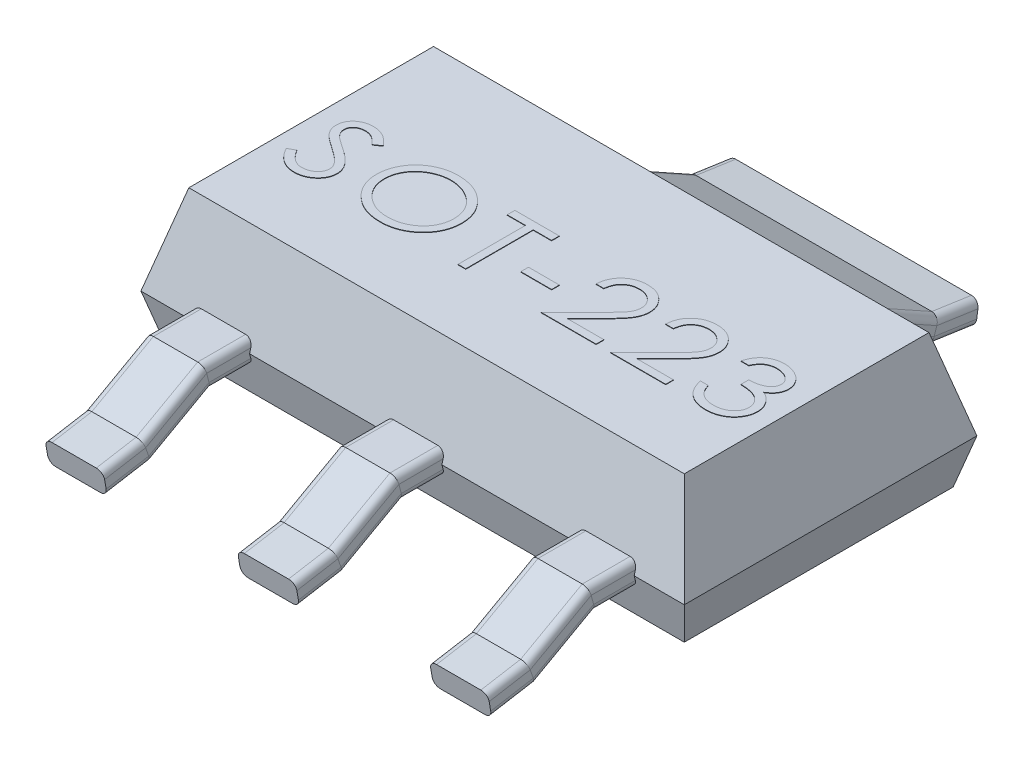
SolidWorks part; units mm, degrees
ref_plane "Front Plane" through (0, 0, 0) normal (0, 0, 1) x (1, 0, 0)
ref_plane "Top Plane" through (0, 0, 0) normal (0, 1, 0) x (1, 0, 0)
ref_plane "Right Plane" through (0, 0, 0) normal (1, 0, 0) x (0, 0, -1)
sketch "Sketch1" plane through (0, 0, 0) normal (0, 1, 0) x (1, 0, 0)
  line L0 (0, 73.9707) -> (0, -64.157) construction
  line L1 (-93.9661, 0) -> (112.1215, 0) construction
  line L3 (3.25, -1.75) -> (-3.25, -1.75)
  line L4 (3.25, -1.75) -> (3.25, 1.75)
  line L5 (3.25, 1.75) -> (-3.25, 1.75)
  line L6 (-3.25, -1.75) -> (-3.25, 1.75)
  line L7 (3.25, -1.75) -> (-3.25, 1.75) construction
  line L8 (3.25, 1.75) -> (-3.25, -1.75) construction
  point P5 (0, 0)
  dimension "D1" = 3.5
  dimension "D2" = 6.5
extrude "Boss-Extrude1" add sketch "Sketch1" along normal blind 1.07 draft 15 and the other way blind 0.53 draft 15
ref_plane "Plane1" through (0, 0, 1.608) normal (0, 0, 1) x (1, 0, 0)
sketch "Sketch4" plane through (0, 0, 1.608) normal (0, 0, 1) x (1, 0, 0)
  line L0 (-3.25, 0) -> (3.25, 0) construction
  line L1 (0.2646, -0.14) -> (-0.2646, -0.14)
  line L2 (0.35, -0.0546) -> (0.35, 0.0546)
  line L3 (0.2646, 0.14) -> (-0.2646, 0.14)
  line L4 (-0.35, -0.0546) -> (-0.35, 0.0546)
  line L5 (0.35, -0.14) -> (-0.35, 0.14) construction
  line L6 (0.35, 0.14) -> (-0.35, -0.14) construction
  line L7 (2.5646, -0.14) -> (2.0354, -0.14)
  line L8 (-2.5646, 0.14) -> (-2.0354, 0.14)
  line L9 (-2.65, 0.0546) -> (-2.65, -0.0546)
  line L10 (-2.5646, -0.14) -> (-2.0354, -0.14)
  line L11 (-1.95, 0.0546) -> (-1.95, -0.0546)
  line L12 (-2.65, 0.14) -> (-1.95, -0.14) construction
  line L13 (-2.65, -0.14) -> (-1.95, 0.14) construction
  line L14 (1.95, 0.0546) -> (1.95, -0.0546)
  line L15 (2.65, 0.0546) -> (2.65, -0.0546)
  line L16 (2.5646, 0.14) -> (2.0354, 0.14)
  line L17 (0, 0.7388) -> (0, -0.4269) construction
  arc A0 (2.65, 0.0546) -> (2.5646, 0.14) centre (2.5646, 0.0546) ccw
  arc A1 (2.65, -0.0546) -> (2.5646, -0.14) centre (2.5646, -0.0546) cw
  arc A2 (0.2646, 0.14) -> (0.35, 0.0546) centre (0.2646, 0.0546) cw
  arc A3 (0.35, -0.0546) -> (0.2646, -0.14) centre (0.2646, -0.0546) cw
  arc A4 (-0.35, -0.0546) -> (-0.2646, -0.14) centre (-0.2646, -0.0546) ccw
  arc A5 (-0.35, 0.0546) -> (-0.2646, 0.14) centre (-0.2646, 0.0546) cw
  arc A6 (-2.5646, 0.14) -> (-2.65, 0.0546) centre (-2.5646, 0.0546) ccw
  arc A7 (-2.65, -0.0546) -> (-2.5646, -0.14) centre (-2.5646, -0.0546) ccw
  arc A8 (-1.95, -0.0546) -> (-2.0354, -0.14) centre (-2.0354, -0.0546) cw
  arc A9 (-1.95, 0.0546) -> (-2.0354, 0.14) centre (-2.0354, 0.0546) ccw
  arc A10 (2.0354, 0.14) -> (1.95, 0.0546) centre (2.0354, 0.0546) ccw
  arc A11 (1.95, -0.0546) -> (2.0354, -0.14) centre (2.0354, -0.0546) ccw
  point P2 (0, 0)
  point P7 (-2.3, 0)
  point P19 (0, 0)
  dimension "D5" = 0.0854
  dimension "D6" = 0.0854
  dimension "D1" = 0.28
  dimension "D2" = 0.7
  dimension "D3" = 0.28
  dimension "D4" = 0.7
sketch "Sketch6" plane through (0, 0, 0) normal (1, 0, 0) x (0, 0, -1)
  line L0 (-1.75, 0) -> (1.75, 0) construction
  line L1 (-1.608, 0) -> (-2.2492, 0)
  line L2 (-2.2492, 0) -> (-2.975, -0.4047)
  line L3 (-2.975, -0.4047) -> (-3.475, -0.49)
  point P8 (-2.4308, -0.4775)
  point P11 (-2.5011, -0.4467)
  point P12 (-2.2492, 0)
  point P13 (-3, -0.4954)
  point P15 (-2.975, -0.4047)
  dimension "D1" = 0.5
  dimension "D2" = 3.475
  dimension "D3" = 0.04
sweep "Sweep1" add profiles "Sketch4" path "Sketch6"
ref_plane "Plane2" through (0, 0, -1.608) normal (0, 0, 1) x (1, 0, 0)
sketch "Sketch9" plane through (0, 0, -1.608) normal (0, 0, 1) x (1, 0, 0)
  line L2 (1.41, 0.14) -> (-1.41, 0.14)
  line L3 (1.5, 0.05) -> (1.5, -0.05)
  line L4 (1.41, -0.14) -> (-1.41, -0.14)
  line L5 (-1.5, 0.05) -> (-1.5, -0.05)
  arc A0 (-1.41, 0.14) -> (-1.5, 0.05) centre (-1.41, 0.05) ccw
  arc A1 (-1.5, -0.05) -> (-1.41, -0.14) centre (-1.41, -0.05) ccw
  arc A2 (1.5, -0.05) -> (1.41, -0.14) centre (1.41, -0.05) cw
  arc A3 (1.5, 0.05) -> (1.41, 0.14) centre (1.41, 0.05) ccw
  point P0 (0, 0)
  point P4 (0, 0)
  dimension "D3" = 0.09
sketch "Sketch10" plane through (0, 0, 0) normal (1, 0, 0) x (0, 0, -1)
  line L2 (-1.608, -0.53) -> (1.608, -0.53) construction
  line L4 (3.005, -0.4173) -> (3.505, -0.49)
  line L5 (2.2567, 0) -> (3.005, -0.4173)
  line L6 (1.608, 0) -> (2.2567, 0)
  point P0 (0, 0)
  dimension "D1" = 0.04
sweep "Sweep2" add profiles "Sketch9" path "Sketch10"
sketch "Sketch12" plane through (0, 1.07, 0) normal (0, 1, 0) x (1, 0, 0)
  line L0 (-2.9633, -0.6521) -> (2.9633, -0.6521) construction
  line L1 (-2.9633, 1.4633) -> (-2.9633, -1.4633) construction
  line L2 (2.9633, -1.4633) -> (2.9633, 1.4633) construction
  text T0 "SOT-223" font "Century Gothic" height 0.9
extrude "Boss-Extrude2" add sketch "Sketch12" along normal blind 0.005
